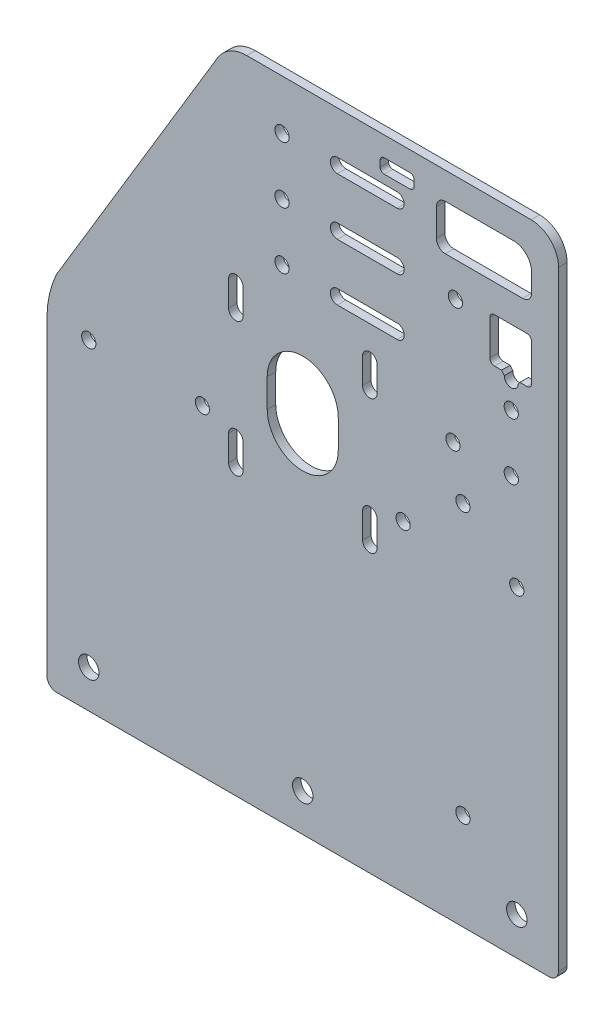
SolidWorks part; units mm, degrees
ref_plane "Front" through (0, 0, 0) normal (0, 0, 1) x (1, 0, 0)
ref_plane "Top" through (0, 0, 0) normal (0, 1, 0) x (1, 0, 0)
ref_plane "Right" through (0, 0, 0) normal (1, 0, 0) x (0, 0, -1)
sketch "Model" plane through (0, 0, 0) normal (0, 0, 1) x (1, 0, 0)
  line L0 (-86.64, 0) -> (86.64, 0)
  line L1 (-90, 112.31) -> (-90, 3.36)
  line L2 (-29.9646, 221.6756) -> (-86.6188, 127.3872)
  line L3 (-26.095, 100.21) -> (-26.095, 109.21)
  line L4 (-26.095, 147.35) -> (-26.095, 156.35)
  line L5 (-21.015, 156.35) -> (-21.015, 147.35)
  line L6 (-21.015, 109.21) -> (-21.015, 100.21)
  line L9 (21.045, 100.21) -> (21.045, 109.21)
  line L10 (21.045, 147.35) -> (21.045, 156.35)
  line L11 (26.125, 156.35) -> (26.125, 147.35)
  line L12 (26.125, 109.21) -> (26.125, 100.21)
  line L13 (27.205, 216.97) -> (27.205, 219.09)
  line L14 (76.385, 175.96) -> (75.818, 175.2497)
  line L15 (39.205, 219.09) -> (39.205, 216.97)
  line L16 (47.015, 205.17) -> (47.015, 214.86)
  line L17 (33.205, 167.44) -> (12.205, 167.44)
  line L18 (12.205, 172.44) -> (33.205, 172.44)
  line L19 (65.815, 178.1211) -> (65.815, 190.45)
  line L20 (78.855, 175.96) -> (76.385, 175.96)
  line L21 (69.945, 176.4611) -> (67.475, 176.4611)
  line L22 (33.205, 187.44) -> (12.205, 187.44)
  line L23 (67.475, 192.11) -> (78.855, 192.11)
  line L24 (80.515, 211.65) -> (80.515, 205.17)
  line L25 (80.515, 190.45) -> (80.515, 177.62)
  line L26 (12.205, 192.44) -> (33.205, 192.44)
  line L27 (77.375, 202.03) -> (50.155, 202.03)
  line L28 (90, 3.36) -> (90, 217.83)
  line L29 (33.205, 207.44) -> (12.205, 207.44)
  line L30 (70.912, 175.2497) -> (69.945, 176.4611)
  line L31 (12.205, 212.44) -> (33.205, 212.44)
  line L32 (37.765, 215.53) -> (28.645, 215.53)
  line L33 (50.155, 218) -> (74.165, 218)
  line L34 (28.645, 220.53) -> (37.765, 220.53)
  line L35 (80.33, 227.5) -> (-19.67, 227.5)
  line L36 (-90, 13.33) -> (90, 13.33) construction
  line L37 (0, 0) -> (0, 227.5) construction
  line L38 (0, 123.28) -> (0, 133.28) construction
  line L39 (-12.5, 123.28) -> (-12.5, 133.28)
  line L40 (12.5, 123.28) -> (12.5, 133.28)
  circle A0 centre (-75.285, 13.33) radius 3.6
  arc A1 (-90, 3.36) -> (-86.64, 0) centre (-86.64, 3.36) ccw
  arc A2 (-26.095, 100.21) -> (-21.015, 100.21) centre (-23.555, 100.21) ccw
  arc A3 (-21.015, 109.21) -> (-26.095, 109.21) centre (-23.555, 109.21) ccw
  arc A4 (-86.6188, 127.3872) -> (-90, 112.31) centre (-53.9604, 112.1455) ccw
  arc A5 (-19.67, 227.5) -> (-29.9646, 221.6756) centre (-19.67, 215.49) ccw
  arc A6 (-21.015, 156.35) -> (-26.095, 156.35) centre (-23.555, 156.35) ccw
  arc A7 (-26.095, 147.35) -> (-21.015, 147.35) centre (-23.555, 147.35) ccw
  circle A8 centre (-7.295, 209.94) radius 2.5
  circle A9 centre (-7.295, 189.94) radius 2.5
  circle A10 centre (-7.295, 169.94) radius 2.5
  circle A11 centre (-35.285, 113.03) radius 2.5
  circle A12 centre (-75.285, 113.03) radius 2.5
  circle A13 centre (75.315, 13.33) radius 3.6
  circle A14 centre (0, 13.33) radius 3.6
  arc A15 (86.64, 0) -> (90, 3.36) centre (86.64, 3.36) ccw
  arc A16 (21.045, 100.21) -> (26.125, 100.21) centre (23.585, 100.21) ccw
  arc A17 (26.125, 109.21) -> (21.045, 109.21) centre (23.585, 109.21) ccw
  circle A18 centre (56.355, 34.03) radius 2.5
  arc A21 (90, 217.83) -> (80.33, 227.5) centre (80.33, 217.83) ccw
  arc A22 (80.515, 211.65) -> (74.165, 218) centre (74.165, 211.65) ccw
  arc A23 (77.375, 202.03) -> (80.515, 205.17) centre (77.375, 205.17) ccw
  arc A24 (47.015, 205.17) -> (50.155, 202.03) centre (50.155, 205.17) ccw
  arc A25 (50.155, 218) -> (47.015, 214.86) centre (50.155, 214.86) ccw
  arc A26 (21.045, 147.35) -> (26.125, 147.35) centre (23.585, 147.35) ccw
  arc A27 (26.125, 156.35) -> (21.045, 156.35) centre (23.585, 156.35) ccw
  arc A28 (33.205, 207.44) -> (33.205, 212.44) centre (33.205, 209.94) ccw
  arc A29 (12.205, 212.44) -> (12.205, 207.44) centre (12.205, 209.94) ccw
  arc A30 (33.205, 187.44) -> (33.205, 192.44) centre (33.205, 189.94) ccw
  arc A31 (12.205, 192.44) -> (12.205, 187.44) centre (12.205, 189.94) ccw
  arc A32 (33.205, 167.44) -> (33.205, 172.44) centre (33.205, 169.94) ccw
  arc A33 (12.205, 172.44) -> (12.205, 167.44) centre (12.205, 169.94) ccw
  circle A34 centre (53.705, 189.94) radius 2.5
  circle A35 centre (73.365, 165.98) radius 2.5
  circle A36 centre (73.365, 145.98) radius 2.5
  circle A37 centre (52.865, 145.98) radius 2.5
  circle A38 centre (56.355, 129.03) radius 2.5
  circle A39 centre (75.315, 113.03) radius 2.5
  circle A40 centre (35.315, 113.03) radius 2.5
  arc A41 (80.515, 190.45) -> (78.855, 192.11) centre (78.855, 190.45) ccw
  arc A42 (78.855, 175.96) -> (80.515, 177.62) centre (78.855, 177.62) ccw
  arc A43 (65.815, 178.1211) -> (67.475, 176.4611) centre (67.475, 178.1211) ccw
  arc A44 (67.475, 192.11) -> (65.815, 190.45) centre (67.475, 190.45) ccw
  arc A45 (39.205, 219.09) -> (37.765, 220.53) centre (37.765, 219.09) ccw
  arc A46 (37.765, 215.53) -> (39.205, 216.97) centre (37.765, 216.97) ccw
  arc A47 (27.205, 216.97) -> (28.645, 215.53) centre (28.645, 216.97) ccw
  arc A48 (28.645, 220.53) -> (27.205, 219.09) centre (28.645, 219.09) ccw
  arc A49 (-12.5, 123.28) -> (12.5, 123.28) centre (0, 123.28) ccw
  arc A50 (12.5, 133.28) -> (-12.5, 133.28) centre (0, 133.28) ccw
  ellipse E0 centre (73.365, 175.2497) end of major axis (75.818, 175.2497) minor radius 2.453 (70.912, 175.2497) -> (75.818, 175.2497) ccw
  point P147 (0, 128.28)
  dimension "D6" = 3.36
  dimension "D7" = 12.01
  dimension "D8" = 9.67
  dimension "D9" = 36.04
  dimension "D11" = 7.2
  dimension "D12" = 13.33
  dimension "D15" = 5
  dimension "D16" = 12.5
  dimension "D26" = 3.14
  dimension "D27" = 9.485
  dimension "D29" = 6.35
  dimension "D32" = 1.44
  dimension "D33" = 6.97
  dimension "D36" = 2.5
  dimension "D43" = 33.645
  dimension "D45" = 2.54
  dimension "D51" = 1.66
  dimension "D52" = 14.7
  dimension "D1" = 180
  dimension "D2" = 227.5
  dimension "D3" = 149
  dimension "D4" = 110
  dimension "D5" = 108.95
  dimension "D10" = 100
  dimension "D13" = 14.715
  dimension "D14" = 14.685
  dimension "D17" = 10
  dimension "D18" = 123.28
  dimension "D19" = 17.56
  dimension "D20" = 97.295
  dimension "D21" = 20
  dimension "D22" = 20
  dimension "D23" = 36.295
  dimension "D24" = 33.5
  dimension "D25" = 15.97
  dimension "D28" = 9.5
  dimension "D30" = 12
  dimension "D31" = 5
  dimension "D34" = 50.795
  dimension "D35" = 19.5
  dimension "D37" = 21
  dimension "D38" = 113.03
  dimension "D39" = 35.315
  dimension "D40" = 40
  dimension "D41" = 35.285
  dimension "D42" = 40
  dimension "D44" = 34.03
  dimension "D46" = 9
  dimension "D47" = 23.555
  dimension "D48" = 19.07
  dimension "D49" = 47.14
  dimension "D50" = 38.14
  dimension "D53" = 9.485
  dimension "D54" = 15.6489
  dimension "D55" = 9.92
  dimension "D56" = 16.15
  dimension "D57" = 0.967
  dimension "D58" = 231.4
  dimension "D59" = 4.906
  dimension "D60" = 1.2114
  dimension "D61" = 20.5
  dimension "D62" = 20
  dimension "D63" = 17.7
  dimension "D64" = 16.635
  dimension "D65" = 33.645
  dimension "D66" = 16
  dimension "D67" = 2.453
  dimension "D68" = 3.42
  dimension "D69" = 3.02
extrude "Boss-Extrude1" add sketch "Model" along normal blind 3
